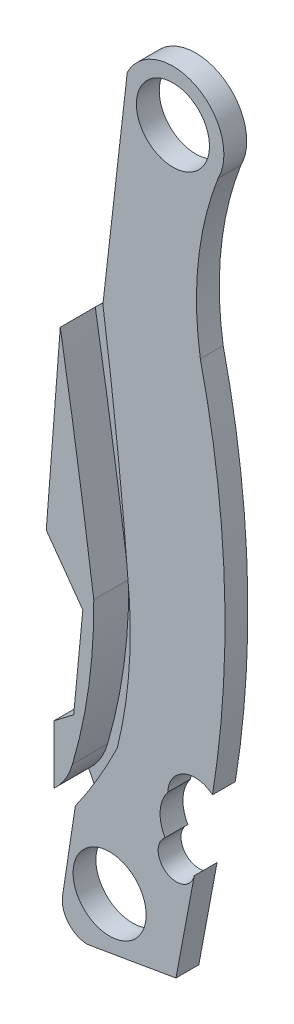
SolidWorks part; units mm, degrees
material "ABS PC"
ref_plane "Front Plane" through (0, 0, 0) normal (0, 0, 1) x (1, 0, 0)
ref_plane "Top Plane" through (0, 0, 0) normal (0, 1, 0) x (1, 0, 0)
ref_plane "Right Plane" through (0, 0, 0) normal (1, 0, 0) x (0, 0, -1)
sketch "Sketch1" plane through (0, 0, 0) normal (0, 0, 1) x (1, 0, 0)
  line L1 (438.5137, 1756.9985) -> (3205.7573, 2047.8476) construction
  line L11 (-5.4927, -17.4943) -> (-5.4927, -22.4219)
  line L12 (-2.6734, 13.3667) -> (-4.9594, 11.2077)
  line L13 (-4.9594, 11.2077) -> (-6.1278, -4.0323)
  line L14 (-6.1278, -4.0323) -> (-3.0798, -8.2741)
  line L15 (-3.0798, -8.2741) -> (-3.8418, -16.2243)
  line L16 (-3.8418, -16.2243) -> (-5.4927, -17.4943)
  line L19 (-4.9085, -23.5903) -> (-6.0261, -30.9563)
  line L20 (4.9466, -24.0983) -> (3.4226, -32.2517)
  line L21 (-2.6734, 13.3667) -> (-0.6414, 31.1467)
  line L22 (-5.4927, -22.4219) -> (-4.9085, -23.5903)
  circle A10 centre (3.1686, 29.2417) radius 3.048
  circle A11 centre (-2.1145, -28.9497) radius 3.048
  arc A12 (-6.0261, -30.9563) -> (-3.9941, -33.5217) centre (-3.9061, -31.3644) ccw
  arc A13 (3.4226, -32.2517) -> (-3.9941, -33.5217) centre (-209.3579, 1188.0949) cw
  arc A14 (2.5082, -22.5743) -> (4.9466, -24.0983) centre (3.4596, -23.7649) ccw
  arc A15 (2.7368, -19.1707) -> (2.5082, -22.5743) centre (5.143, -21.0417) ccw
  arc A16 (6.4706, -17.4943) -> (2.7368, -19.1707) centre (5.021, -19.2618) ccw
  arc A17 (5.4546, 13.4937) -> (6.4706, -17.4943) centre (-73.0065, -4.5894) cw
  arc A18 (5.4546, 13.4937) -> (6.9278, 27.2605) centre (31.8009, 17.6366) cw
  arc A19 (-0.6414, 31.1467) -> (6.9278, 27.2605) centre (3.1633, 29.2428) cw
  dimension "D1" = 4.2545
  dimension "D12" = 26.67
  dimension "D14" = 80.518
  dimension "D26" = 1238.758
  dimension "D27" = 2.286
  dimension "D28" = 3.048
  dimension "D29" = 1.524
  dimension "D41" = 2.159
  dimension "D47" = 6.096
  dimension "D45" = 58.1914
  dimension "D2" = 1.905
  dimension "D3" = 3.81
  dimension "D4" = 1.9812
  dimension "D5" = 3.7592
  dimension "D6" = 17.78
  dimension "D7" = 2.032
  dimension "D8" = 2.159
  dimension "D9" = 2.286
  dimension "D10" = 15.24
  dimension "D11" = 1.1684
  dimension "D13" = 15.748
  dimension "D15" = 46.736
  dimension "D16" = 37.5158
  dimension "D17" = 6.2484
  dimension "D18" = 45.466
  dimension "D19" = 7.0104
  dimension "D20" = 3.9116
  dimension "D21" = 1.8796
  dimension "D22" = 5.5372
  dimension "D23" = 5.3594
  dimension "D24" = 0.5842
  dimension "D25" = 1.1684
  dimension "D30" = 8.1534
  dimension "D31" = 53.34
  dimension "D32" = 1.524
  dimension "D33" = 1.778
  dimension "D34" = 2.286
  dimension "D35" = 1.016
  dimension "D36" = 3.7338
  dimension "D37" = 3.4036
  dimension "D38" = 1.524
  dimension "D39" = 2.4384
  dimension "D40" = 1.651
  dimension "D42" = 2.0066
  dimension "D43" = 1.27
  dimension "D44" = 1.27
extrude "Boss-Extrude1" add sketch "Sketch1" along normal blind 1.905
sketch "Sketch2" plane through (0, 0, 1.905) normal (0, 0, 1) x (1, 0, 0)
  line L3 (-7.0599, -26.7145) -> (-7.4994, -23.5141)
  line L4 (-4.9594, 11.2077) -> (-2.6734, 13.3667)
  arc A6 (-2.1654, -7.0803) -> (-4.9594, 11.2077) centre (-573.4556, -85.0033) ccw
  arc A7 (-2.1654, -7.0803) -> (-3.9434, -19.8565) centre (-45.8512, -7.5125) cw
  arc A8 (-7.4994, -23.5141) -> (-3.9434, -19.8565) centre (-9.0802, -18.4197) ccw
  arc A9 (-7.0599, -26.7145) -> (-1.4719, -18.0785) centre (-38.6491, -0.1485) ccw
  arc A10 (-0.4559, -6.9787) -> (-1.4719, -18.0785) centre (-37.4741, -9.1867) cw
  arc A11 (-2.6734, 13.3667) -> (-0.4559, -6.9787) centre (-335.9787, -33.2532) cw
  dimension "D8" = 336.55
  dimension "D9" = 576.58
  dimension "D10" = 43.688
  dimension "D11" = 37.084
  dimension "D12" = 1.016
  dimension "D13" = 41.275
  dimension "D17" = 5.334
  dimension "D18" = 3.2304
  dimension "D1" = 40.0812
  dimension "D2" = 2.794
  dimension "D3" = 18.288
  dimension "D4" = 34.7218
  dimension "D5" = 3.6576
  dimension "D6" = 3.556
  dimension "D7" = 19.7358
  dimension "D14" = 8.636
  dimension "D15" = 5.588
  dimension "D16" = 6.604
extrude "Cut-Extrude1" cut sketch "Sketch2" against normal blind 1.651
sketch "Sketch3" plane through (0, 0, 1.905) normal (0, 0, 1) x (1, 0, 0)
  line L5 (-5.4927, -17.4943) -> (-5.4927, -22.3671)
  line L6 (-4.9593, 11.2077) -> (-6.1278, -4.0323)
  line L7 (-6.1278, -4.0323) -> (-3.0798, -8.2741)
  line L8 (-3.0798, -8.2741) -> (-3.8418, -16.2243)
  line L9 (-3.8418, -16.2243) -> (-5.4927, -17.4943)
  line L10 (-5.4927, -17.4943) -> (-5.4927, -22.3671)
  line L12 (-4.9593, 11.2077) -> (-6.1278, -4.0323)
  line L13 (-6.1278, -4.0323) -> (-3.0798, -8.2741)
  line L14 (-3.0798, -8.2741) -> (-3.8418, -16.2243)
  line L15 (-3.8418, -16.2243) -> (-5.4927, -17.4943)
  arc A3 (-3.9433, -19.8565) -> (-2.1653, -7.0803) centre (-45.8512, -7.5125) ccw
  arc A4 (-2.1653, -7.0803) -> (-4.9593, 11.2077) centre (-573.4556, -85.0033) ccw
  arc A5 (-5.4927, -22.3671) -> (-3.9433, -19.8565) centre (-9.0802, -18.4197) ccw
  arc A6 (-3.9433, -19.8565) -> (-2.1653, -7.0803) centre (-45.8512, -7.5125) ccw
  arc A7 (-2.1653, -7.0803) -> (-4.9593, 11.2077) centre (-573.4556, -85.0033) ccw
  arc A8 (-5.4927, -22.3671) -> (-3.9433, -19.8565) centre (-9.0802, -18.4197) ccw
  dimension "D1" = 0
extrude "Boss-Extrude2" add sketch "Sketch3" along normal blind 1.27
